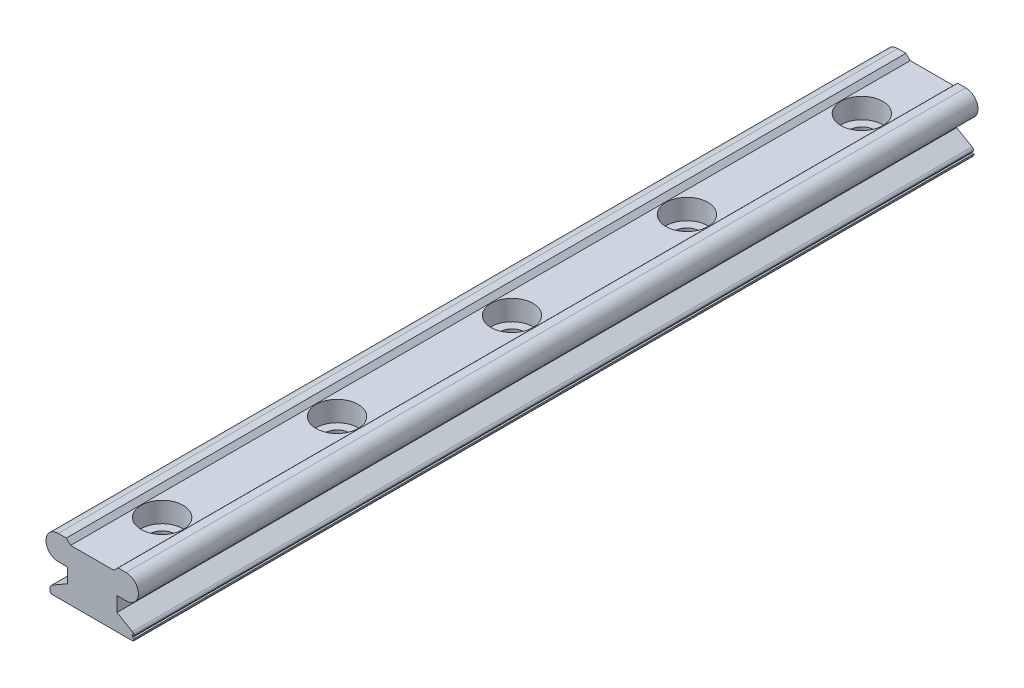
SolidWorks part; units mm, degrees
ref_plane "Front" through (0, 0, 0) normal (0, 0, 1) x (1, 0, 0)
ref_plane "Top" through (0, 0, 0) normal (0, 1, 0) x (1, 0, 0)
ref_plane "Right" through (0, 0, 0) normal (1, 0, 0) x (0, 0, -1)
sketch "Sketch1" plane through (0, 0, 0) normal (0, 0, 1) x (1, 0, 0)
  line L0 (-4.85, 8) -> (-3.7, 8)
  line L1 (-4.85, 4.5) -> (-3.55, 4.5)
  line L2 (-3.55, 4.5) -> (-3.55, 2.4145)
  line L3 (6, 0.7067) -> (6, 0.254)
  line L4 (5.746, 0) -> (-5.746, 0)
  line L5 (-6, 0.254) -> (-6, 0.7067)
  line L6 (-3.55, 2.4145) -> (-5.746, 1.1466)
  line L7 (4.85, 4.5) -> (3.55, 4.5)
  line L8 (-12.992, 13) -> (-6.6, 13) construction
  line L9 (13.5, 12.492) -> (13.5, 9.2) construction
  line L10 (12.992, 2.3) -> (5.5483, 2.3) construction
  line L11 (-12.992, 2.3) -> (-5.5483, 2.3) construction
  line L12 (-13.5, 2.808) -> (-13.5, 6) construction
  line L13 (-13.5, 9.2) -> (-13.246, 9.2) construction
  line L14 (-13.246, 9.2) -> (-13.246, 6) construction
  line L15 (-13.246, 6) -> (-13.5, 6) construction
  line L16 (13.5, 9.2) -> (13.246, 9.2) construction
  line L17 (13.246, 9.2) -> (13.246, 6) construction
  line L18 (13.246, 6) -> (13.5, 6) construction
  line L19 (-13.5, 9.2) -> (-13.5, 12.492) construction
  line L20 (13.5, 6) -> (13.5, 2.808) construction
  line L21 (3.55, 4.5) -> (3.55, 2.4145)
  line L22 (3.55, 2.4145) -> (5.746, 1.1466)
  line L23 (-3.7, 8) -> (-3.0787, 7.4)
  line L24 (-3.0787, 7.4) -> (3.0787, 7.4)
  line L25 (3.0787, 7.4) -> (3.7, 8)
  line L26 (3.7, 8) -> (4.85, 8)
  line L27 (-5.5483, 2.3) -> (-4.05, 3.1651) construction
  line L28 (-4.05, 3.1651) -> (-4.05, 4.45) construction
  line L29 (6, 0) -> (6, 1) construction
  line L30 (-4.85, 8.05) -> (-3.2, 8.05) construction
  line L31 (-3.2, 8.05) -> (-3.2, 8.6) construction
  line L32 (-3.2, 8.6) -> (3.2, 8.6) construction
  line L33 (3.2, 8.6) -> (3.2, 8.05) construction
  line L34 (3.2, 8.05) -> (4.85, 8.05) construction
  line L35 (4.85, 4.45) -> (4.05, 4.45) construction
  line L36 (-4.85, 4.45) -> (-4.05, 4.45) construction
  line L39 (4.05, 4.45) -> (4.05, 3.1651) construction
  line L42 (4.05, 3.1651) -> (5.5483, 2.3) construction
  line L43 (-6.6, 13) -> (-6.6, 12.746) construction
  line L46 (-6.6, 12.746) -> (-3.4, 12.746) construction
  line L47 (-3.4, 12.746) -> (-3.4, 13) construction
  line L48 (3.4, 13) -> (3.4, 12.746) construction
  line L49 (3.4, 12.746) -> (6.6, 12.746) construction
  line L50 (6.6, 12.746) -> (6.6, 13) construction
  line L51 (-3.4, 13) -> (3.4, 13) construction
  line L52 (6.6, 13) -> (12.992, 13) construction
  arc A0 (-4.85, 8) -> (-4.85, 4.5) centre (-4.85, 6.25) ccw
  arc A1 (4.85, 8) -> (4.85, 4.5) centre (4.85, 6.25) cw
  arc A2 (-6, 0.7067) -> (-5.746, 1.1466) centre (-5.492, 0.7067) cw
  arc A3 (6, 0.7067) -> (5.746, 1.1466) centre (5.492, 0.7067) ccw
  arc A4 (12.992, 2.3) -> (13.5, 2.808) centre (12.992, 2.808) ccw construction
  arc A5 (13.5, 12.492) -> (12.992, 13) centre (12.992, 12.492) ccw construction
  arc A6 (-12.992, 2.3) -> (-13.5, 2.808) centre (-12.992, 2.808) cw construction
  arc A7 (-13.5, 12.492) -> (-12.992, 13) centre (-12.992, 12.492) cw construction
  arc A8 (-5.746, 0) -> (-6, 0.254) centre (-5.746, 0.254) cw
  arc A9 (5.746, 0) -> (6, 0.254) centre (5.746, 0.254) ccw
  arc A10 (-4.85, 8.05) -> (-4.85, 4.45) centre (-4.85, 6.25) ccw construction
  arc A11 (4.85, 8.05) -> (4.85, 4.45) centre (4.85, 6.25) cw construction
  point P2 (0, 8.6)
  point P7 (0, 7.4)
  point P26 (-6.6, 6.25)
  point P27 (6.6, 6.25)
  point P35 (0, 13)
  point P39 (-7.78, 6.31)
  point P40 (-5.45, 6.31)
  point P42 (-7.78, 13.45)
  point P43 (-5.7798, 13.45)
  point P46 (5.7798, 13.45)
  point P47 (7.78, 13.45)
  point P49 (7.78, 6.31)
  point P50 (5.45, 6.31)
  dimension "D7" = 0.508
  dimension "D3" = 0.254
  dimension "D5" = 0.05
  dimension "D1" = 0.254
  dimension "Rail Wd" = 12
  dimension "Rail Ht" = 8
  dimension "D2" = 30
  dimension "Oall Rail Wd" = 13.2
  dimension "Oall Ht" = 13
  dimension "Rail Offset" = 1
  dimension "Side Groove Offset" = 3.7
  dimension "Rail Neck Wd" = 7.1
  dimension "D4" = 136
  dimension "Rail Nose Thickness" = 3.5
  dimension "Rail Trough Dp" = 0.6
  dimension "Rail Trough Wd" = 7.4
  dimension "Side Groove Ht" = 3.2
  dimension "Carriage Trough Wd" = 6.4
  dimension "Carriage Trough Dp" = 0.6
  dimension "Top Groove Offset" = 6.9
  dimension "Oall Wd" = 27
  dimension "Carriage Ht" = 10.7
  dimension "Carriage Neck Wd" = 8.1
  dimension "Angle Offset" = 0.9
extrude "Boss-Extrude1" add sketch "Sketch1" along normal mid plane 120
sketch "Sketch4" plane through (0, 0, 0) normal (0, 0, 1) x (1, 0, 0)
  line L0 (6, 0.254) -> (6, 0.7067) construction
  line L1 (6, 0.4064) -> (5.746, 0.4064)
  line L2 (6, 0.4064) -> (6, 0.7874)
  line L3 (6, 0.7874) -> (5.746, 0.7874)
  line L4 (5.746, 0.4064) -> (5.746, 0.7874)
  line L5 (-5.746, 0) -> (5.746, 0) construction
  dimension "Notch Offset" = 0.4064
  dimension "D2" = 0.254
  dimension "D3" = 0.381
extrude "Cut-Extrude1" cut sketch "Sketch4" against normal through all and the other way through all
sketch "Sketch2" plane through (0, 0, 0) normal (1, 0, 0) x (0, 0, -1)
  line L0 (-53, 7.4) -> (-53, 4.5)
  line L1 (-53, 4.5) -> (-51.75, 4.5)
  line L2 (-51.75, 4.5) -> (-51.75, 0)
  line L3 (-51.75, 0) -> (-50, 0)
  line L4 (-50, 0) -> (-50, 7.4)
  line L5 (-50, 7.4) -> (-53, 7.4) construction
  line L6 (-60, 7.4) -> (60, 7.4) construction
  line L7 (-53, 7.4) -> (-47, 7.4) construction
  line L8 (-51.75, 0) -> (-48.25, 0) construction
  line L9 (-60, 0) -> (60, 0) construction
  line L10 (-60, 0) -> (60, 0) construction
  line L14 (-60, 8) -> (-60, 4.5) construction
  line L15 (-53, 7.4) -> (-53, 8)
  line L16 (-60, 8) -> (60, 8) construction
  line L17 (-53, 8) -> (-50, 8)
  line L18 (-50, 8) -> (-50, 7.4)
  dimension "Top Hole Dp" = 2.9
  dimension "Top Hole Dia" = 6
  dimension "Bottom Hole Dia" = 3.5
  dimension "Hole Offset" = 10
revolve "Cut-Revolve1" cut sketch "Sketch2" angle 360 mid plane about L4
pattern_linear "LPattern2" count 5 spacing 25 along (0, 0, -1) of "Cut-Revolve1"
sketch "Sketch3" plane through (0, 0, 0) normal (1, 0, 0) x (0, 0, -1)
  line L2 (-53, 4.5) -> (-53, 7.4)
  line L7 (-47, 4.5) -> (-47, 7.4)
  line L13 (-47, 4.5) -> (-53, 4.5) construction
  line L14 (-48.25, 0) -> (-48.25, 4.5) construction
  line L15 (-51.75, 4.5) -> (-51.75, 0) construction
  line L18 (-47, 4.5) -> (-53, 4.5)
  line L19 (-48.25, 0) -> (-48.25, 4.5)
  line L20 (-51.75, 4.5) -> (-51.75, 0)
  line L21 (-60, 7.4) -> (60, 7.4)
  line L22 (60, 4.5) -> (60, 8) construction
mirror "K15" [suppressed] about plane through (0, 0, 0) normal (1, 0, 0)
